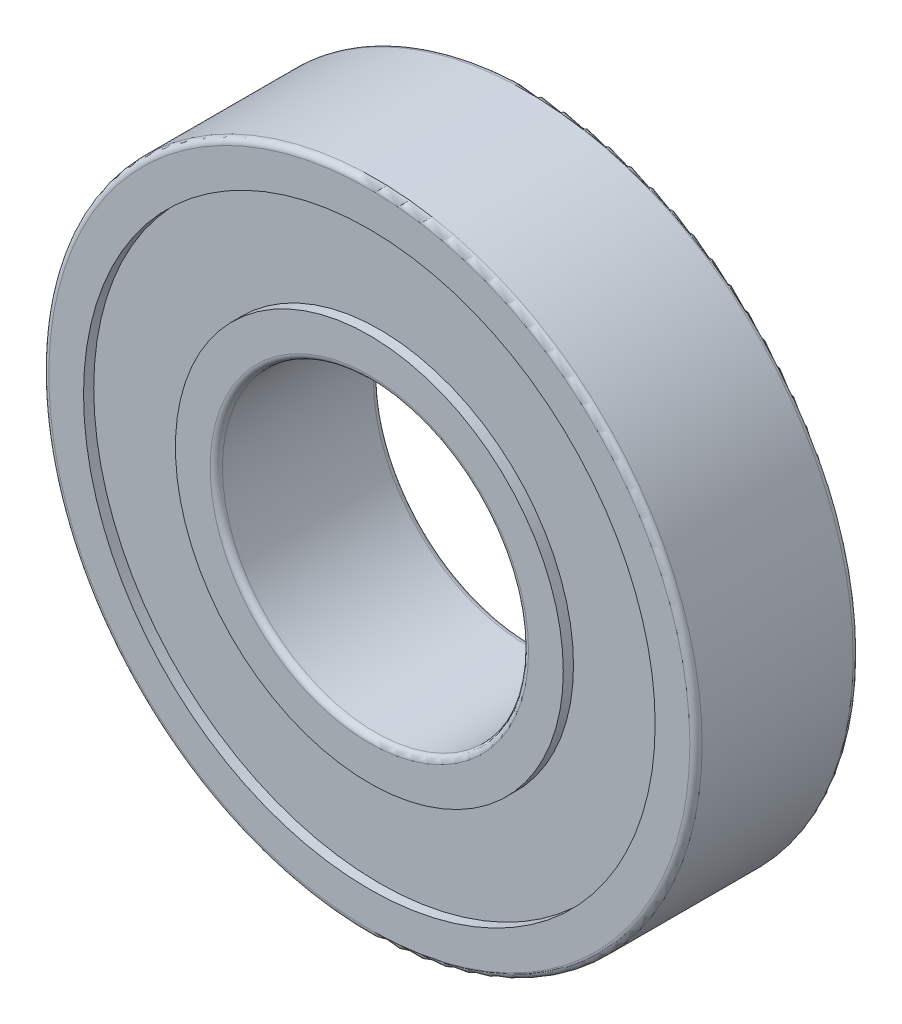
SolidWorks part; units mm, degrees
material "Chrome Stainless Steel"
ref_plane "Front Plane" through (0, 0, 0) normal (0, 0, 1) x (1, 0, 0)
ref_plane "Top Plane" through (0, 0, 0) normal (0, 1, 0) x (1, 0, 0)
ref_plane "Right Plane" through (0, 0, 0) normal (1, 0, 0) x (0, 0, -1)
sketch "Sketch1" plane through (0, 0, 0) normal (0, 0, 1) x (1, 0, 0)
  circle A0 centre (0, 0) radius 16
  circle A1 centre (0, 0) radius 7.5
  dimension "D1" = 32
  dimension "D2" = 15
extrude "Boss-Extrude1" add sketch "Sketch1" along normal mid plane 8
sketch "Sketch2" plane through (0, 0, 4) normal (0, 0, 1) x (1, 0, 0)
  circle A0 centre (0, 0) radius 14
  circle A1 centre (0, 0) radius 9.5
  dimension "D1" = 28
  dimension "D2" = 19
extrude "Cut-Extrude1" cut sketch "Sketch2" against normal blind 0.5
fillet "Fillet1" radius 0.3 4 edges at (7.5, 0, 4) (16, 0, 4) (16, 0, -4) (7.5, 0, -4)
mirror "Mirror4" about plane through (0, 0, 0) normal (0, 0, 1) of "Cut-Extrude1"
